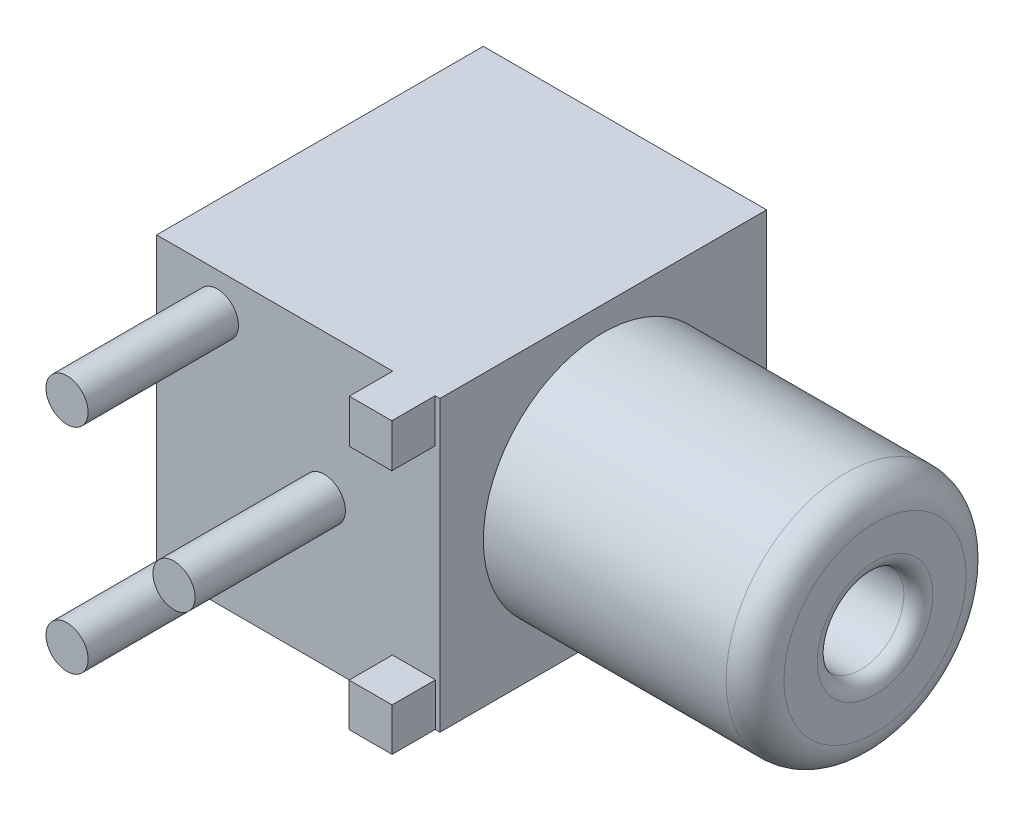
SolidWorks part; units mm, degrees
ref_plane "Front Plane" through (0, 0, 0) normal (0, 0, 1) x (1, 0, 0)
ref_plane "Top Plane" through (0, 0, 0) normal (0, 1, 0) x (1, 0, 0)
ref_plane "Right Plane" through (0, 0, 0) normal (1, 0, 0) x (0, 0, -1)
sketch "Sketch3" [suppressed] plane through (0, 0, 0) normal (0, 0, 1) x (1, 0, 0)
  line L1 (50.6252, 20.01) -> (52.0948, 20.01)
  line L2 (50.6252, 20.01) -> (50.6252, 21.51)
  line L3 (50.6252, 21.51) -> (52.0948, 21.51)
  line L4 (52.0948, 20.01) -> (52.0948, 21.51)
  line L5 (50.6168, 11.5182) -> (52.1032, 11.5182)
  line L6 (50.6168, 11.5182) -> (50.6168, 13.0018)
  line L7 (50.6168, 13.0018) -> (52.1032, 13.0018)
  line L8 (52.1032, 11.5182) -> (52.1032, 13.0018)
  line L9 (50.6168, 11.5182) -> (52.1032, 13.0018) construction
  line L10 (50.6168, 13.0018) -> (52.1032, 11.5182) construction
  line L11 (50.6252, 20.01) -> (52.0948, 21.51) construction
  line L12 (50.6252, 21.51) -> (52.0948, 20.01) construction
  line L15 (42.46, 11.51) -> (52.26, 11.51)
  line L16 (42.46, 21.51) -> (42.46, 11.51)
  line L17 (52.26, 21.51) -> (42.46, 21.51)
  line L18 (61.66, 20.51) -> (52.26, 20.51)
  line L19 (52.26, 11.51) -> (52.26, 21.51)
  line L20 (52.26, 12.51) -> (61.66, 12.51)
  line L21 (61.66, 12.51) -> (61.66, 20.51)
  circle A4 centre (44.56, 20.21) radius 0.729
  circle A5 centre (44.56, 12.81) radius 0.729
  circle A6 centre (48.26, 16.51) radius 0.729
  circle A13 centre (48.26, 16.51) radius 0.829
  circle A14 centre (44.56, 12.81) radius 0.829
  circle A15 centre (44.56, 20.21) radius 0.829
  circle A16 centre (51.36, 20.76) radius 1.05
  circle A17 centre (51.36, 12.26) radius 1.05
  dimension "D5" = 1.658
  dimension "D6" = 1.658
  dimension "D7" = 1.658
  dimension "D8" = 2.1
  dimension "D9" = 2.1
  dimension "D1" = 10
  dimension "D2" = 9.8
  dimension "D3" = 9.4
  dimension "D4" = 8
  dimension "D10" = 0.1
  dimension "D11" = 0.1
  dimension "D12" = 0.1
sketch "Sketch5" plane through (0, 0, 0) normal (0, 0, 1) x (1, 0, 0)
  circle A0 centre (44.56, 20.21) radius 0.729
  circle A1 centre (44.56, 12.81) radius 0.729
  circle A2 centre (48.26, 16.51) radius 0.729
extrude "Boss-Extrude1" add sketch "Sketch5" along normal blind 5.2
sketch "Sketch6" plane through (0, 0, 0) normal (0, 0, 1) x (1, 0, 0)
  line L0 (42.46, 11.51) -> (52.26, 11.51)
  line L1 (42.46, 21.51) -> (42.46, 11.51)
  line L2 (52.26, 21.51) -> (42.46, 21.51)
  line L3 (52.26, 11.51) -> (52.26, 21.51)
extrude "Boss-Extrude2" add sketch "Sketch6" against normal blind 11.3
sketch "Sketch7" plane through (52.26, 0, 0) normal (1, 0, 0) x (0, 0, -1)
  line L2 (11.3, 11.51) -> (11.3, 21.51) construction
  line L5 (11.3, 21.51) -> (0, 21.51) construction
  circle A0 centre (5.65, 16.51) radius 4.15
  dimension "D1" = 8.3
  dimension "D2" = 5.65
  dimension "D3" = 5
sketch "Sketch8" plane through (52.26, 0, 0) normal (1, 0, 0) x (0, 0, -1)
  circle A0 centre (5.65, 16.51) radius 4.15
extrude "Boss-Extrude3" add sketch "Sketch8" along normal blind 9.4
sketch "Sketch9" plane through (61.66, 0, 0) normal (1, 0, 0) x (0, 0, -1)
  circle A0 centre (5.65, 16.51) radius 1.5
  dimension "D1" = 3
extrude "Cut-Extrude1" cut sketch "Sketch9" against normal blind 9.4
fillet "Fillet1" radius 1 1 edges at (61.66, 16.51, -9.8)
fillet "Fillet2" radius 0.5 1 edges at (61.66, 16.51, -7.15)
sketch "Sketch10" plane through (0, 0, 0) normal (0, 0, 1) x (1, 0, 0)
  line L0 (50.6252, 20.01) -> (52.0948, 20.01)
  line L1 (50.6252, 20.01) -> (50.6252, 21.51)
  line L2 (50.6252, 21.51) -> (52.0948, 21.51)
  line L3 (52.0948, 20.01) -> (52.0948, 21.51)
  line L4 (50.6168, 11.5182) -> (52.1032, 11.5182)
  line L5 (50.6168, 11.5182) -> (50.6168, 13.0018)
  line L6 (50.6168, 13.0018) -> (52.1032, 13.0018)
  line L7 (52.1032, 11.5182) -> (52.1032, 13.0018)
extrude "Boss-Extrude4" add sketch "Sketch10" along normal blind 1.5
